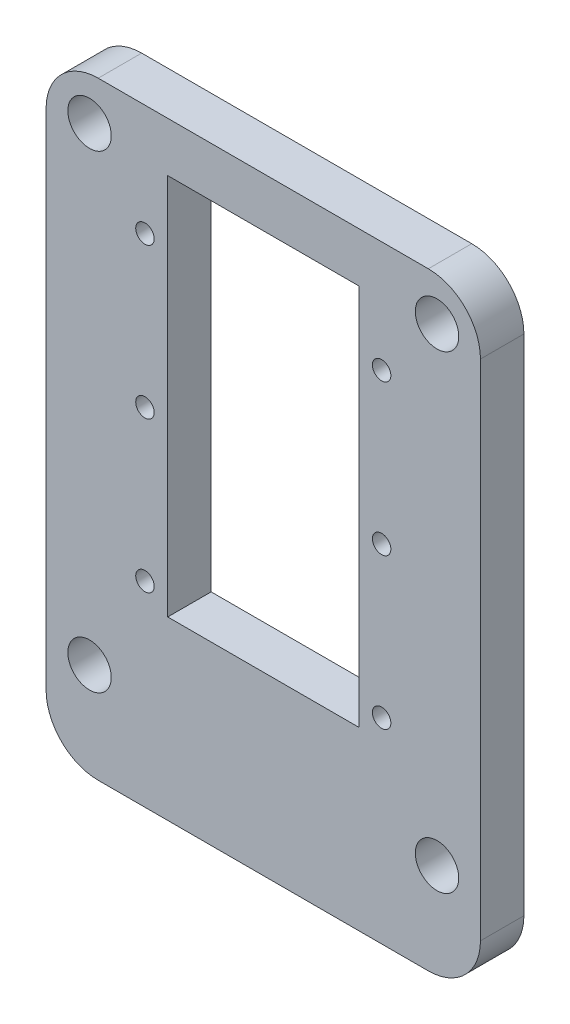
SolidWorks part; units mm, degrees
ref_plane "Front Plane" through (0, 0, 0) normal (0, 0, 1) x (1, 0, 0)
ref_plane "Top Plane" through (0, 0, 0) normal (0, 1, 0) x (1, 0, 0)
ref_plane "Right Plane" through (0, 0, 0) normal (1, 0, 0) x (0, 0, -1)
sketch "Sketch1" plane through (0, 0, 0) normal (0, 0, 1) x (1, 0, 0)
  line L0 (-19.6989, 23.2988) -> (-14.85, 29.7515)
  line L1 (-13.2512, 30.55) -> (13.2512, 30.55)
  line L2 (-20.1, 22.0973) -> (-20.1, -22.0973)
  line L3 (-13.2512, -30.55) -> (13.2512, -30.55)
  line L4 (20.1, 22.0973) -> (20.1, -22.0973)
  line L5 (-20.1, 30.55) -> (20.1, -30.55) construction
  line L6 (-20.1, -30.55) -> (20.1, 30.55) construction
  line L7 (14.85, 29.7515) -> (19.6989, 23.2988)
  line L8 (19.6989, -23.2988) -> (14.85, -29.7515)
  line L9 (-14.85, -29.7515) -> (-19.6989, -23.2988)
  arc A0 (-19.6989, -23.2988) -> (-20.1, -22.0973) centre (-18.1, -22.0973) cw
  arc A1 (-14.85, -29.7515) -> (-13.2512, -30.55) centre (-13.2512, -28.55) ccw
  arc A2 (14.85, -29.7515) -> (13.2512, -30.55) centre (13.2512, -28.55) cw
  arc A3 (19.6989, -23.2988) -> (20.1, -22.0973) centre (18.1, -22.0973) ccw
  arc A4 (19.6989, 23.2988) -> (20.1, 22.0973) centre (18.1, 22.0973) cw
  arc A5 (14.85, 29.7515) -> (13.2512, 30.55) centre (13.2512, 28.55) ccw
  arc A6 (-14.85, 29.7515) -> (-13.2512, 30.55) centre (-13.2512, 28.55) cw
  arc A7 (-19.6989, 23.2988) -> (-20.1, 22.0973) centre (-18.1, 22.0973) ccw
  point P0 (0, 0)
  point P16 (-20.1, -22.765)
  point P19 (-14.25, -30.55)
  point P22 (14.25, -30.55)
  point P25 (20.1, -22.765)
  point P28 (20.1, 22.765)
  point P31 (14.25, 30.55)
  point P34 (-14.25, 30.55)
  point P37 (-20.1, 22.765)
  dimension "D11" = 2
  dimension "D1" = 40.2
  dimension "D2" = 61.1
  dimension "D3" = 5.85
  dimension "D4" = 7.785
  dimension "D5" = 5.85
  dimension "D6" = 7.785
  dimension "D7" = 7.785
  dimension "D8" = 5.85
  dimension "D9" = 5.85
  dimension "D10" = 7.785
extrude "Boss-Extrude1" add sketch "Sketch1" against normal blind 6.35
sketch "Sketch2" plane through (0, 0, -6.35) normal (0, 0, -1) x (-1, 0, 0)
  line L0 (14.85, 29.7515) -> (14.85, -29.7515) construction
  line L1 (-14.85, 29.7515) -> (-14.85, -29.7515) construction
  line L2 (19.6989, 23.2988) -> (-19.6989, 23.2988) construction
  line L3 (20.1, -22.0973) -> (-20.1, -22.0973) construction
  line L4 (0, 30.55) -> (0, -30.55) construction
  line L5 (-13.2512, 30.55) -> (13.2512, 30.55) construction
  line L6 (13.2512, -30.55) -> (-13.2512, -30.55) construction
  circle A0 centre (17.3, 21.9488) radius 1.35
  circle A1 centre (17.3, -0.0512) radius 1.35
  circle A2 centre (17.3, -22.0512) radius 1.35
  circle A3 centre (11, -27.75) radius 1.385
  circle A4 centre (-11, -27.75) radius 1.385
  circle A5 centre (-17.3, -22.0512) radius 1.35
  circle A6 centre (-17.3, -0.0512) radius 1.35
  circle A7 centre (-17.3, 21.9488) radius 1.35
  dimension "D1" = 2.7
  dimension "D5" = 2.77
  dimension "D2" = 22
  dimension "D3" = 22
  dimension "D4" = 17.3
  dimension "D6" = 11
  dimension "D7" = 2.8
extrude "Cut-Extrude1" cut sketch "Sketch2" against normal through all
sketch "Sketch3" plane through (0, 0, -6.35) normal (0, 0, -1) x (-1, 0, 0)
  line L2 (-31.75, 38.2048) -> (31.75, 38.2048)
  line L3 (-31.75, 38.2048) -> (-31.75, -50.6952)
  line L4 (-31.75, -50.6952) -> (31.75, -50.6952)
  line L6 (31.75, 38.2048) -> (31.75, -50.6952)
  line L9 (-19.1605, 23.6188) -> (19.1605, 23.6188)
  line L10 (-19.1605, 23.6188) -> (-19.1605, -23.6188)
  line L11 (-19.1605, -23.6188) -> (19.1605, -23.6188)
  line L12 (19.1605, 23.6188) -> (19.1605, -23.6188)
  circle A0 centre (17.3, 21.9488) radius 1.35 construction
  point P0 (0, 0)
  point P6 (0, 0)
  dimension "D4" = 16.256
  dimension "D1" = 63.5
  dimension "D2" = 88.9
  dimension "D3" = 31.75
extrude "Boss-Extrude2" add sketch "Sketch3" against normal blind 6.35
sketch "Sketch5" plane through (0, 0, 0) normal (0, 0, 1) x (1, 0, 0)
  line L1 (-13.97, 30.9488) -> (13.97, 30.9488)
  line L2 (-13.97, 30.9488) -> (-13.97, -24.9312)
  line L3 (-13.97, -24.9312) -> (13.97, -24.9312)
  line L4 (13.97, 30.9488) -> (13.97, -24.9312)
  circle A0 centre (17.3, 21.9488) radius 1.35 construction
  dimension "D1" = 27.94
  dimension "D2" = 55.88
  dimension "D3" = 9
extrude "Cut-Extrude3" cut sketch "Sketch5" against normal through all
sketch "Sketch6" plane through (0, 0, -6.35) normal (0, 0, -1) x (-1, 0, 0)
  line L0 (-13.97, 30.9488) -> (13.97, 30.9488) construction
  line L1 (31.75, 38.2048) -> (-31.75, 38.2048) construction
  circle A0 centre (25.4, 31.8548) radius 3.175
  circle A1 centre (-25.4, 31.8548) radius 3.175
  circle A2 centre (-25.4, -36.7252) radius 3.175
  circle A3 centre (25.4, -36.7252) radius 3.175
  point P4 (0, 30.9488)
  dimension "D1" = 25.4
  dimension "D2" = 6.35
  dimension "D7" = 6.35
  dimension "D5" = 50.8
  dimension "D6" = 68.58
  dimension "D3" = 2
  dimension "D4" = 2
extrude "Cut-Extrude4" cut sketch "Sketch6" against normal through all
fillet "Fillet2" radius 7.62 4 edges at (-31.75, -50.6952, -3.175) (31.75, -50.6952, -3.175) (-31.75, 38.2048, -3.175) (31.75, 38.2048, -3.175)
